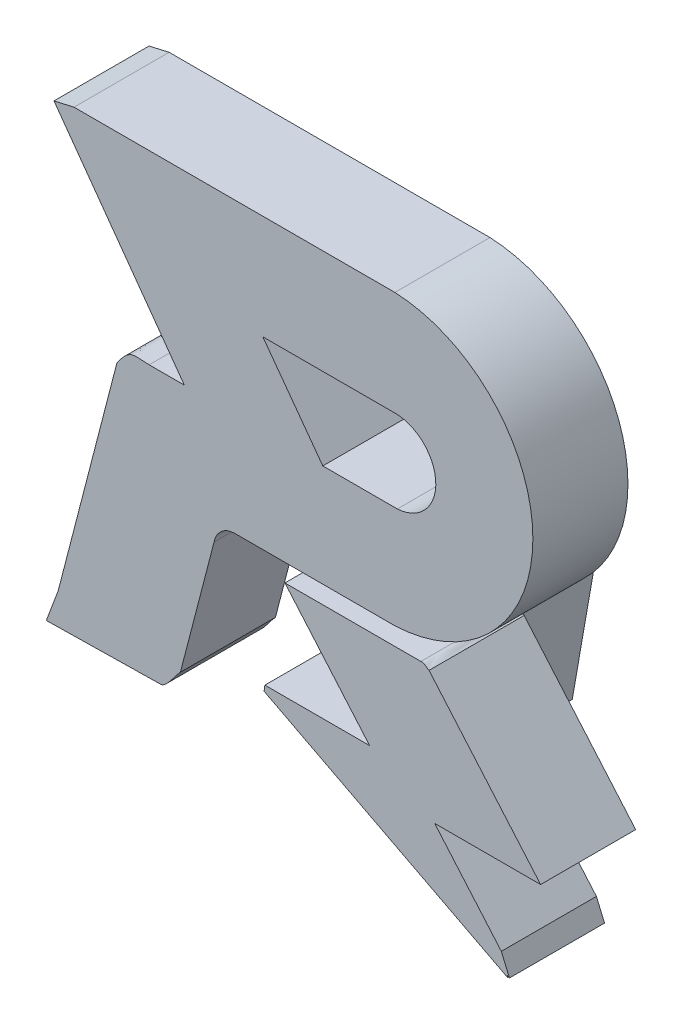
SolidWorks part; units mm, degrees
ref_plane "前视基准面" through (0, 0, 0) normal (0, 0, 1) x (1, 0, 0)
ref_plane "上视基准面" through (0, 0, 0) normal (0, 1, 0) x (1, 0, 0)
ref_plane "右视基准面" through (0, 0, 0) normal (1, 0, 0) x (0, 0, -1)
sketch "草图1" plane through (0, 0, 0) normal (0, 0, 1) x (1, 0, 0)
  line L0 (0.8157, 10.0927) -> (24.2227, 10.0927) construction
  line L1 (0, 0) -> (6, 0.1018)
  line L2 (0, 0) -> (0.6209, 1.6528)
  line L3 (0.6209, 1.6528) -> (3.7135, 13.5907)
  line L4 (7.2573, 14.3476) -> (5.4079, 14.3476)
  line L5 (7.2573, 14.3476) -> (0.4028, 23.8632)
  line L6 (0.4028, 23.8632) -> (1.4574, 24.1043)
  line L7 (1.4574, 24.1043) -> (18.3281, 24.1043)
  line L8 (18.3281, 24.1043) -> (18.3281, 8.9224) construction
  line L9 (18.3281, 8.9224) -> (10.1053, 8.9224)
  line L10 (12.546, 7.9837) -> (17, 2.8024)
  line L11 (17, 2.8024) -> (11.5817, 2.8024)
  line L12 (11.5817, 2.8024) -> (11.4924, 2.8024)
  line L13 (11.4924, 2.8024) -> (11.45, 2.5021)
  line L14 (11.45, 2.5021) -> (24.2595, -4.1344)
  line L15 (24.2595, -4.1344) -> (24.2292, -4.0391)
  line L16 (24.2292, -4.0391) -> (24.3548, -4.1042)
  line L17 (24.3548, -4.1042) -> (23.9259, -3.1033)
  line L18 (23.9259, -3.1033) -> (20.4215, 0.9709)
  line L19 (20.4215, 0.9709) -> (25.9912, 0.9709)
  line L20 (25.9912, 0.9709) -> (20.1249, 7.7911)
  line L21 (12.546, 7.9837) -> (19.6976, 7.9837)
  line L22 (7.0484, 1.1662) -> (8.8216, 7.9837)
  line L23 (11.3854, 18.6114) -> (14.5395, 14.3081)
  line L24 (14.5395, 14.3081) -> (18.4588, 14.3081)
  line L25 (11.3854, 18.6114) -> (18.3281, 18.6114)
  arc A0 (18.3281, 24.1043) -> (18.3281, 8.9224) centre (17.9868, 16.5133) cw
  arc A1 (18.3281, 18.6114) -> (18.4588, 14.3081) centre (18.3281, 16.4578) cw
  spline S0 degree 3 poles (3.7135, 13.5907) (3.8741, 13.8142) (4.3816, 14.5347) (4.958, 14.3476) (5.4079, 14.3476) knots 0 0 0 0 0.493225 1 1 1 1
  spline S1 degree 3 poles (6, 0.1018) (6.117, 0.1038) (6.5393, 0.4454) (6.7669, 0.8707) (7.0484, 1.1662) knots 0 0 0 0 0.218981 1 1 1 1
  spline S2 degree 3 poles (8.8216, 7.9837) (8.8805, 8.2927) (9.1332, 8.6841) (9.6747, 8.9195) (9.9454, 8.9224) (10.1053, 8.9224) knots 0 0 0 0 0.545723 0.722751 1 1 1 1
  spline S3 degree 3 poles (19.6976, 7.9837) (19.8827, 8.0277) (19.9769, 7.8503) (20.1249, 7.7911) knots 0 0 0 0 1 1 1 1
extrude "凸台-拉伸1" add sketch "草图1" along normal blind 5
scale "缩放比例3" bodies to scale 102 101 scale about origin uniform scaling yes scale factor 2
scale "缩放比例4" bodies to scale 107 108 scale about origin uniform scaling yes scale factor 1.2
sketch "草图2" plane through (0, 0, 0) normal (0, 0, -1) x (-1, 0, 0)
  line L0 (-30.1103, 19.1609) -> (-44.3766, 2.5653)
  line L1 (-30.1103, 19.1609) -> (-40.8001, 6.7258) construction
  line L2 (-44.3766, 2.5653) -> (-47.087, 18.088) construction
  line L3 (-44.3766, 2.5653) -> (-47.2743, 19.1609)
  line L4 (-47.2743, 19.1609) -> (-30.1103, 19.1609)
  line L5 (-40.0661, 21.4137) -> (-24.2526, 21.4137)
  line L6 (-24.2526, 21.4137) -> (-43.9875, 21.4137) construction
  line L7 (-41.3966, 18.088) -> (-40.0661, 21.4137) construction
  line L8 (-24.2526, 21.4137) -> (-17.4175, 34.4342)
  line L9 (-17.4175, 34.4342) -> (-34.8948, 34.3394)
  line L10 (-34.8948, 34.3394) -> (-40.0661, 21.4137)
extrude "凸台-拉伸2" add sketch "草图2" along normal blind 10
sketch "草图3" plane through (27.8257, 14.6072, 0) normal (-0.8854, -0.4648, 0) x (0, 0, 1)
  line L0 (-10, 20.6958) -> (0, 22.3929)
  line L1 (-2.2405, 7.6874) -> (-10, 20.6958) construction
  line L2 (-10, 7.6874) -> (-10, 22.3929) construction
  line L3 (0, 22.3929) -> (-10, 22.3929)
  line L4 (-10, 22.3929) -> (-10, 20.6958)
sketch "草图4" plane through (41.9229, 16.7724, 0) normal (0.9285, 0.3715, 0) x (0, 0, -1)
  line L0 (10, 17.4043) -> (0, 18.9207)
  line L1 (10, 17.4043) -> (2.2405, 4.9989) construction
  line L2 (0, 18.9207) -> (10, 18.9207)
  line L3 (10, 18.9207) -> (10, 17.4043)
  line L4 (10, 18.9207) -> (10, 4.9989) construction
loft "切除-放样1" cut profiles "草图3", "草图4"
